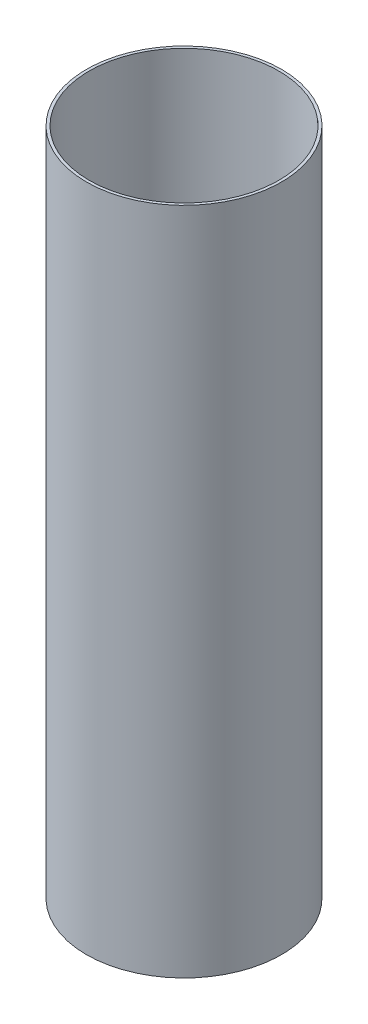
SolidWorks part; units mm, degrees
ref_plane "Front Plane" through (0, 0, 0) normal (0, 0, 1) x (1, 0, 0)
ref_plane "Top Plane" through (0, 0, 0) normal (0, 1, 0) x (1, 0, 0)
ref_plane "Right Plane" through (0, 0, 0) normal (1, 0, 0) x (0, 0, -1)
sketch "Sketch1" plane through (0, 0, 0) normal (0, 1, 0) x (1, 0, 0)
  circle A0 centre (0, 0) radius 17
  circle A1 centre (0, 0) radius 17.5
  dimension "D1" = 35
  dimension "D2" = 0.5
extrude "Boss-Extrude1" add sketch "Sketch1" along normal mid plane 120
